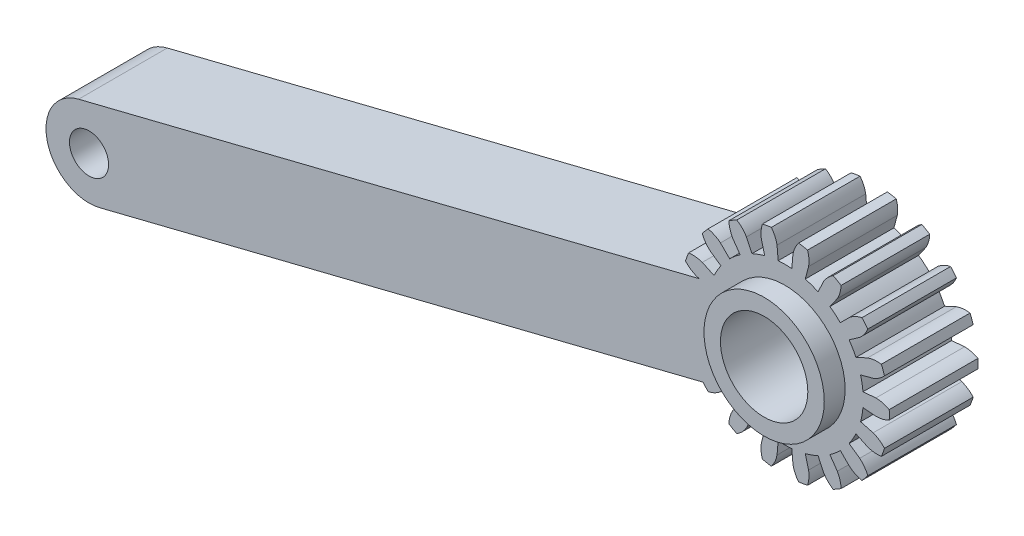
SolidWorks part; units mm, degrees
ref_plane "Front Plane" through (0, 0, 0) normal (0, 0, 1) x (1, 0, 0)
ref_plane "Top Plane" through (0, 0, 0) normal (0, 1, 0) x (1, 0, 0)
ref_plane "Right Plane" through (0, 0, 0) normal (1, 0, 0) x (0, 0, -1)
sketch "Sketch2" plane through (0, 0, 0) normal (0, 0, 1) x (1, 0, 0)
  line L0 (-8.89, -27.432) -> (2.3825, -27.432) construction
  line L1 (-8.89, -27.432) -> (2.3826, -27.9242) construction
  line L2 (-8.89, -27.432) -> (1.6824, -28.357) construction
  line L3 (-8.89, -27.432) -> (1.8033, -29.3175) construction
  line L4 (0, -5.08) -> (0, -20.0564) construction
  line L5 (22.225, -5.08) -> (-22.225, -5.08) construction
  line L6 (0, -20.0564) -> (0, -37.8471) construction
  line L7 (-4.8877, -28.1377) -> (-1.3858, -28.7552)
  line L8 (-1.299, -28.0961) -> (-0.0375, -28.2065)
  line L10 (-1.299, -26.7679) -> (-0.0375, -26.6575)
  line L11 (-4.8877, -26.7263) -> (-1.3858, -26.1088)
  circle A0 centre (-8.89, -27.432) radius 7.62 construction
  circle A1 centre (-8.89, -27.432) radius 8.89 construction
  circle A2 centre (-8.89, -27.432) radius 10.16 construction
  circle A3 centre (-8.89, -27.432) radius 4.064 construction
  arc A4 (-1.3858, -28.7552) -> (-1.299, -28.0961) centre (-8.89, -27.432) ccw
  arc A5 (1.2603, -26.9888) -> (1.2603, -27.8752) centre (-8.89, -27.432) cw
  arc A6 (1.2603, -27.8752) -> (-0.0375, -28.2065) centre (-0.0595, -25.4126) cw
  arc A7 (1.2603, -26.9888) -> (-0.0375, -26.6575) centre (-0.0595, -29.4514) ccw
  arc A8 (-1.3858, -26.1088) -> (-1.299, -26.7679) centre (-8.89, -27.432) cw
  circle A9 centre (-8.89, -27.432) radius 4.064 construction
  arc A10 (-4.8877, -28.1377) -> (-4.8877, -26.7263) centre (-8.89, -27.432) ccw
  dimension "D4" = 1.27
  dimension "D5" = 1.27
  dimension "D6" = 2.794
  dimension "D7" = 4.064
  dimension "D1" = 2.5
  dimension "D2" = 5
  dimension "D3" = 10
extrude "Boss-Extrude1" add sketch "Sketch2" along normal up to surface (12.7 mm away)
pattern_circular "CirPattern1" count 18 over 360 about axis through (-8.89, -27.432, 0) along (0, 0, 1) of "Boss-Extrude1"
ref_axis "Axis1" through (-8.89, -27.432, 12.7) along (0, 0, -1)
ref_plane "Plane1" through (0, -27.432, 0) normal (0, -1, 0) x (0, 0, -1)
sketch "Sketch3" plane through (0, -27.432, 0) normal (0, -1, 0) x (0, 0, -1)
  line L0 (-12.7, -15.0766) -> (-12.7, 15.0766) construction
  line L1 (-12.7, 1.826) -> (-10.668, 1.826)
  line L2 (-12.7, 1.826) -> (-12.7, -3.0341)
  line L3 (-12.7, -3.0341) -> (-10.668, -3.0341)
  line L4 (-10.668, 1.826) -> (-10.668, -3.0341)
  line L5 (-6.35, 1.2603) -> (-6.35, -7.1389) construction
  line L6 (-12.7, 1.2603) -> (0, 1.2603) construction
  line L8 (0, 1.826) -> (-2.032, 1.826)
  line L9 (0, 1.826) -> (0, -3.0341)
  line L10 (-2.032, 1.826) -> (-2.032, -3.0341)
  line L11 (0, -3.0341) -> (-2.032, -3.0341)
revolve "Cut-Revolve1" cut sketch "Sketch3" angle 360 about axis through (-8.89, -27.432, 12.7) along (0, 0, -1)
ref_plane "Plane2" through (0, 0, 6.35) normal (0, 0, 1) x (1, 0, 0)
sketch "Sketch5" plane through (0, 0, 6.35) normal (0, 0, 1) x (1, 0, 0)
  line L0 (-8.89, -27.432) -> (-76.6611, -44.3466) construction
  line L1 (-11.8432, -32.4886) -> (-75.6462, -48.4128)
  line L2 (-13.873, -24.3561) -> (-77.676, -40.2803)
  arc A1 (-77.676, -40.2803) -> (-75.6462, -48.4128) centre (-76.6611, -44.3466) ccw
  circle A3 centre (-76.6611, -44.3466) radius 1.905
  arc A5 (-11.8432, -32.4886) -> (-13.873, -24.3561) centre (-8.89, -27.432) cw
  point P3 (-42.7755, -35.8893)
  dimension "D2" = 3.81
  dimension "D3" = 2.286
  dimension "D1" = 69.85
extrude "Boss-Extrude3" add sketch "Sketch5" along normal mid plane 8.636
sketch "Sketch6" plane through (0, 0, 2.032) normal (0, 0, -1) x (-1, 0, 0)
  circle A0 centre (8.89, -27.432) radius 5.8559
extrude "Cut-Extrude1" cut sketch "Sketch6" along normal up to surface (2.032 mm away) up to face at (-4.826, -27.432, 0)
sketch "Sketch7" plane through (0, 0, 12.7) normal (0, 0, 1) x (1, 0, 0)
  circle A0 centre (-8.89, -27.432) radius 4.2545
  dimension "D1" = 8.509
extrude "Cut-Extrude2" cut sketch "Sketch7" against normal through all
